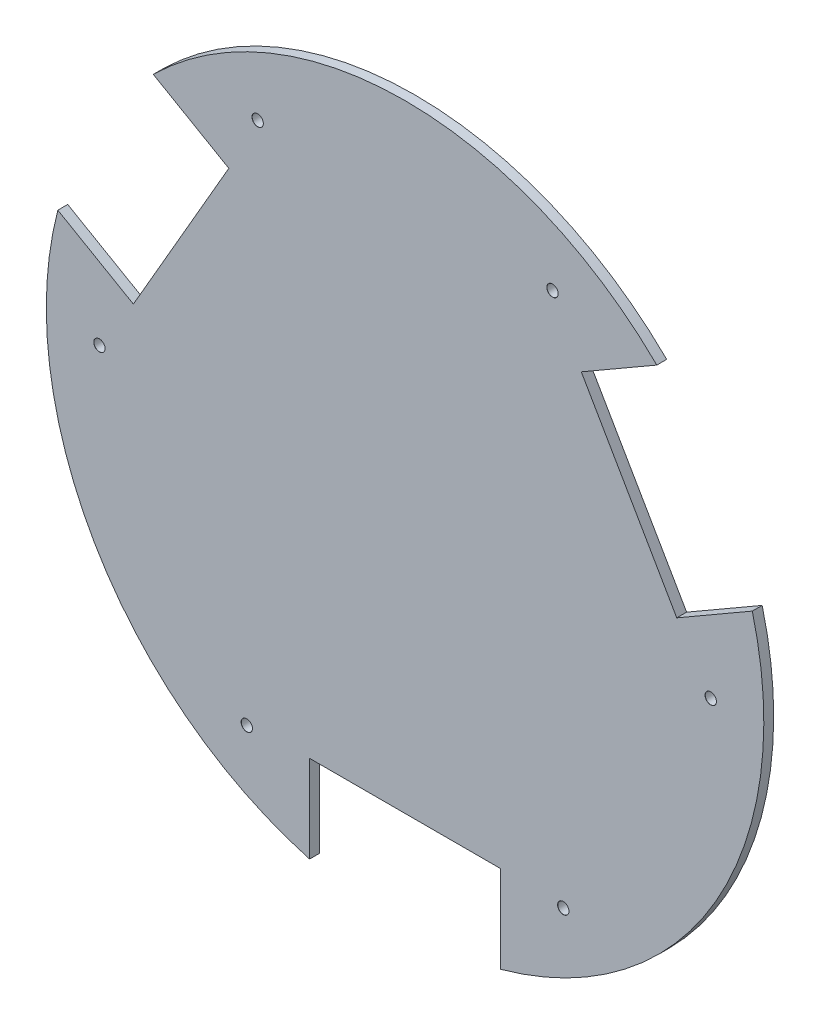
SolidWorks part; units mm, degrees
ref_plane "Plan de face" through (0, 0, 0) normal (0, 0, 1) x (1, 0, 0)
ref_plane "Plan de dessus" through (0, 0, 0) normal (0, 1, 0) x (1, 0, 0)
ref_plane "Plan de droite" through (0, 0, 0) normal (1, 0, 0) x (0, 0, -1)
sketch "Esquisse2" plane through (0, 0, 0) normal (0, 0, 1) x (1, 0, 0)
  circle A0 centre (0, 0) radius 109
  dimension "D1" = 218
extrude "Boss.-Extru.1" add sketch "Esquisse2" along normal blind 3
sketch "Esquisse3" plane through (0, 0, 3) normal (0, 0, 1) x (1, 0, 0)
  line L0 (0, 148.1699) -> (0, -178.9257) construction
  line L1 (-29, -120.9891) -> (29, -120.9891)
  line L2 (-29, -120.9891) -> (-29, -78.5714)
  line L3 (-29, -78.5714) -> (29, -78.5714)
  line L4 (29, -120.9891) -> (29, -78.5714)
  line L5 (-90.2796, 85.6093) -> (-119.2796, 35.3798)
  line L6 (-90.2796, 85.6093) -> (-53.5448, 64.4004)
  line L7 (-53.5448, 64.4004) -> (-82.5448, 14.171)
  line L8 (-119.2796, 35.3798) -> (-82.5448, 14.171)
  line L9 (119.2796, 35.3798) -> (90.2796, 85.6093)
  line L10 (119.2796, 35.3798) -> (82.5448, 14.171)
  line L11 (82.5448, 14.171) -> (53.5448, 64.4004)
  line L12 (90.2796, 85.6093) -> (53.5448, 64.4004)
  point P18 (0, 0)
  dimension "D1" = 3
  dimension "D2" = 58
  dimension "D3" = 78.5714
extrude "Enlèv. mat.-Extru.1" cut sketch "Esquisse3" against normal blind 3
sketch "Esquisse4" plane through (0, 0, 3) normal (0, 0, 1) x (1, 0, 0)
  circle A0 centre (0, 0) radius 92.8499
hole_wizard "Dégagement M31" positions "Esquisse5" profile "Esquisse6" hole size "M3" standard "ISO" end condition through all
sketch "Esquisse5" plane through (0, 0, 3) normal (0, 0, 1) x (1, 0, 0)
  circle A0 centre (0, 0) radius 92.8499 construction
  point P0 (-48.0882, -79.4269)
  point P5 (48.069, -79.4269)
  point P8 (48.1162, -79.4269)
  point P9 (48.0869, -79.4269)
  point P10 (48.069, -79.4269)
sketch "Esquisse6" plane through (-48.0882, -79.4269, 3) normal (1, 0, 0) x (0, -1, 0)
  line L0 (0, 0) -> (0, 3)
  line L1 (0, 3) -> (1.7, 3)
  line L2 (1.7, 3) -> (1.7, 0.025)
  line L3 (1.7, 0.025) -> (1.725, 0)
  line L5 (1.725, 0) -> (0, 0)
  line L6 (-1.7, 0.025) -> (-1.725, 0) construction
  line L11 (0, -6.35) -> (0, 107.95) construction
  dimension "Diamètre du perçage jusqu'au prochain" = 3.4
  dimension "Profondeur du perçage jusqu'au prochain" = 3
  dimension "Diamètre du fraisage entrant" = 3.45
  dimension "Angle du fraisage entrant" = 90
pattern_circular "Répétition circulaire1" count 3 over 360 about axis through (0, 0.0461, 0) along (0, 0, 1) of "Dégagement M31"
